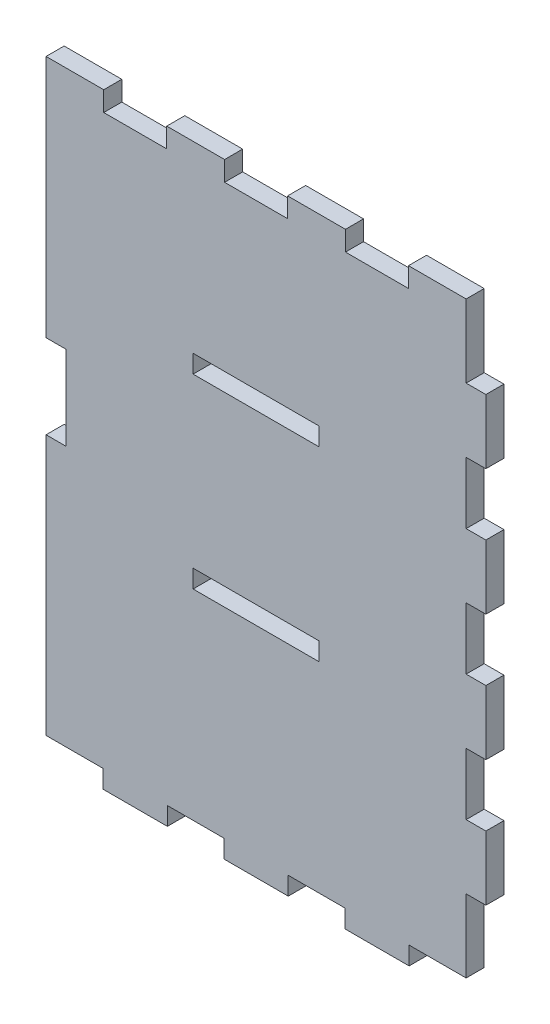
SolidWorks part; units mm, degrees
ref_plane "Front Plane" through (0, 0, 0) normal (0, 0, 1) x (1, 0, 0)
ref_plane "Top Plane" through (0, 0, 0) normal (0, 1, 0) x (1, 0, 0)
ref_plane "Right Plane" through (0, 0, 0) normal (1, 0, 0) x (0, 0, -1)
sketch "Sketch2" plane through (0, 0, 0) normal (0, 0, 1) x (1, 0, 0)
  line L0 (100, 0) -> (100, 17.35)
  line L1 (0, 0) -> (13.575, 0)
  line L2 (0, 0) -> (0, 62)
  line L3 (0, 140) -> (13.725, 140)
  line L34 (28.725, 140) -> (42.5, 140)
  line L35 (13.725, 135.3) -> (28.725, 135.3)
  line L36 (13.725, 135.3) -> (13.725, 140)
  line L38 (28.725, 135.3) -> (28.725, 140)
  line L39 (57.5, 135.3) -> (57.5, 140)
  line L40 (42.5, 135.3) -> (57.5, 135.3)
  line L41 (42.5, 135.3) -> (42.5, 140)
  line L42 (86.275, 135.3) -> (86.275, 140)
  line L43 (71.275, 135.3) -> (86.275, 135.3)
  line L44 (71.275, 135.3) -> (71.275, 140)
  line L45 (57.5, 140) -> (71.275, 140)
  line L46 (86.275, 140) -> (100, 140)
  line L47 (28.875, 0) -> (42.35, 0)
  line L48 (13.575, -4.3) -> (28.875, -4.3)
  line L49 (13.575, -4.3) -> (13.575, 0)
  line L51 (28.875, -4.3) -> (28.875, 0)
  line L52 (57.65, -4.3) -> (57.65, 0)
  line L53 (42.35, -4.3) -> (57.65, -4.3)
  line L54 (42.35, -4.3) -> (42.35, 0)
  line L55 (86.425, -4.3) -> (86.425, 0)
  line L56 (71.125, -4.3) -> (86.425, -4.3)
  line L57 (71.125, -4.3) -> (71.125, 0)
  line L58 (57.65, 0) -> (71.125, 0)
  line L59 (86.425, 0) -> (100, 0)
  line L60 (100, 122.65) -> (100, 140)
  line L61 (100, 107.35) -> (104.7, 107.35)
  line L63 (0, 93.9) -> (0, 90.8)
  line L68 (35, 47.7) -> (35, 52)
  line L71 (100, 122.65) -> (104.7, 122.65)
  line L72 (104.7, 107.35) -> (104.7, 122.65)
  line L73 (100, 77.35) -> (104.7, 77.35)
  line L74 (100, 92.65) -> (104.7, 92.65)
  line L75 (104.7, 77.35) -> (104.7, 92.65)
  line L76 (100, 47.35) -> (104.7, 47.35)
  line L77 (100, 62.65) -> (104.7, 62.65)
  line L78 (104.7, 47.35) -> (104.7, 62.65)
  line L79 (100, 17.35) -> (104.7, 17.35)
  line L80 (100, 32.65) -> (104.7, 32.65)
  line L81 (104.7, 17.35) -> (104.7, 32.65)
  line L85 (100, 92.65) -> (100, 107.35)
  line L86 (100, 62.65) -> (100, 77.35)
  line L87 (100, 32.65) -> (100, 47.35)
  line L89 (65, 52) -> (35, 52)
  line L90 (65, 47.7) -> (35, 47.7)
  line L91 (65, 96.3) -> (35, 96.3)
  line L92 (65, 92) -> (35, 92)
  line L93 (35, 96.3) -> (35, 92)
  line L94 (65, 52) -> (65, 47.7)
  line L95 (65, 96.3) -> (65, 92)
  line L96 (0, 82) -> (0, 140)
  line L97 (0, 62) -> (4.7, 62)
  line L99 (0, 82) -> (4.7, 82)
  line L100 (4.7, 62) -> (4.7, 82)
  line L101 (50, 92) -> (50, 52) construction
  point P31 (50, 52)
  point P36 (21.225, -4.3)
  point P67 (4.7, 72)
  point P68 (50, 72)
  point P69 (104.7, 115)
  point P70 (104.7, 85)
  point P72 (50, -4.3)
  point P73 (21.225, 135.3)
  point P74 (50, 135.3)
  dimension "D1" = 140
  dimension "D2" = 100
  dimension "D3" = 4.7
  dimension "D4" = 15.3
  dimension "D5" = 25
  dimension "D6" = 4
  dimension "D7" = 30
  dimension "D8" = 15
  dimension "D9" = 4.7
  dimension "D10" = 21.225
  dimension "D11" = 3
  dimension "D12" = 28.775
  dimension "D13" = 15.3
  dimension "D14" = 4.3
  dimension "D15" = 21.225
  dimension "D16" = 28.775
  dimension "D17" = 4.3
  dimension "D18" = 4.3
  dimension "D19" = 47.7
  dimension "D20" = 40
  dimension "D22" = 30
  dimension "D23" = 50
  dimension "D24" = 20
  dimension "D25" = 4.7
  dimension "D21" = 3
extrude "Boss-Extrude1" add sketch "Sketch2" along normal blind 4.3
